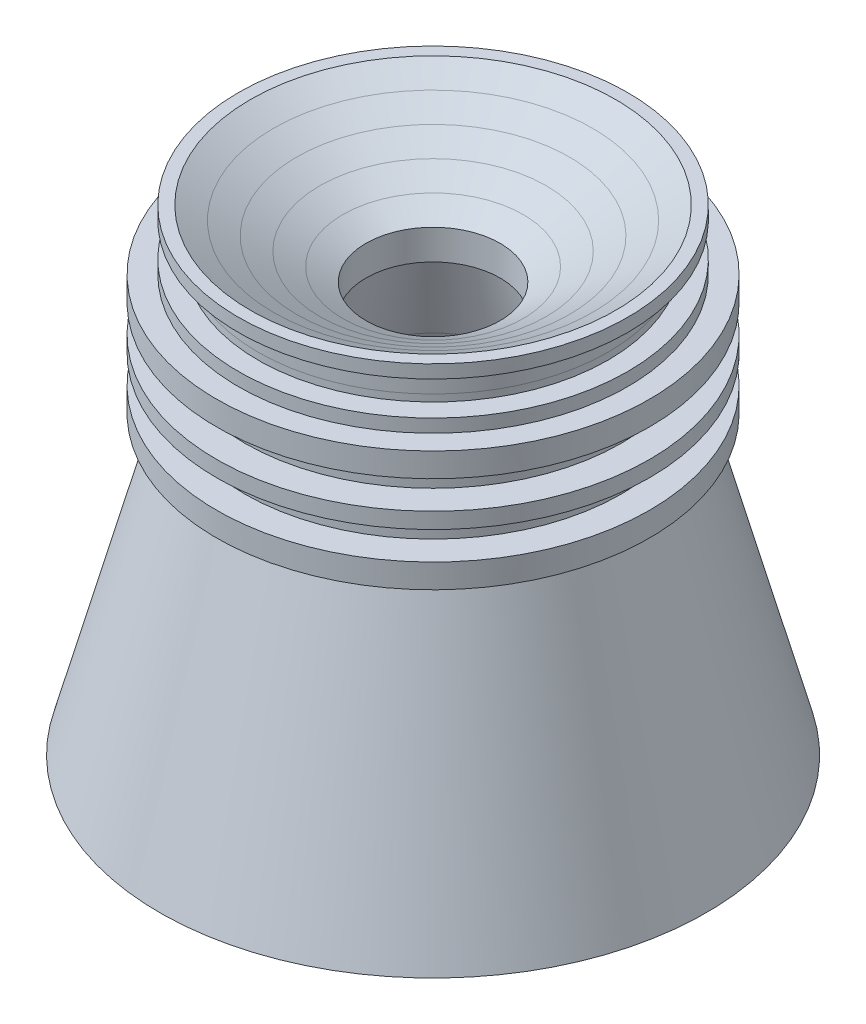
SolidWorks part; units mm, degrees
material "Copper"
ref_plane "Front Plane" through (0, 0, 0) normal (0, 0, 1) x (1, 0, 0)
ref_plane "Top Plane" through (0, 0, 0) normal (0, 1, 0) x (1, 0, 0)
ref_plane "Right Plane" through (0, 0, 0) normal (1, 0, 0) x (0, 0, -1)
sketch "Sketch1" plane through (0, 0, 0) normal (0, 0, 1) x (1, 0, 0)
  line L0 (0, 50.323) -> (0, -50.323) construction
  line L1 (41.1353, 50.323) -> (38.5953, 50.323)
  line L2 (38.5953, 50.323) -> (14.1732, 36.2228)
  line L3 (14.1732, 36.2228) -> (14.1732, 29.8728)
  line L4 (14.1732, 29.8728) -> (35.6616, -50.323)
  line L7 (41.0679, 11.9714) -> (41.1353, 12.223)
  line L9 (41.1353, 12.223) -> (45.7327, 12.223)
  line L10 (45.7327, 12.223) -> (45.7327, 37.623)
  line L11 (45.7327, 37.623) -> (41.1353, 37.623)
  line L12 (41.1353, 37.623) -> (41.1353, 50.323)
  line L13 (0, 50.323) -> (38.5953, 50.323) construction
  line L14 (41.0679, 11.9714) -> (57.7596, -50.323)
  line L15 (57.7596, -50.323) -> (35.6616, -50.323)
  line L16 (0, -50.323) -> (35.6616, -50.323) construction
  point P4 (0, 0)
  dimension "D1" = 41.1353
  dimension "D2" = 60
  dimension "D3" = 15
  dimension "D4" = 6.35
  dimension "D5" = 35.6616
  dimension "D6" = 14.1732
  dimension "D7" = 2.54
  dimension "D8" = 4.5974
  dimension "D9" = 22.098
  dimension "D10" = 150
  dimension "D11" = 12.7
  dimension "D12" = 25.4
revolve "Revolve1" add sketch "Sketch1" angle 360 about L0
sketch "Sketch2" plane through (0, 0, 0) normal (0, 0, 1) x (1, 0, 0)
  line L0 (45.7327, 12.223) -> (45.7327, 37.623) construction
  line L1 (41.1353, 47.5417) -> (36.9824, 47.5417)
  line L2 (41.1353, 47.5417) -> (41.1353, 40.4043)
  line L3 (41.1353, 40.4043) -> (36.9824, 40.4043)
  line L4 (36.9824, 47.5417) -> (36.9824, 40.4043)
  line L5 (45.7327, 32.543) -> (39.7915, 32.543)
  line L6 (45.7327, 32.543) -> (45.7327, 26.6018)
  line L7 (45.7327, 26.6018) -> (39.7915, 26.6018)
  line L8 (39.7915, 32.543) -> (39.7915, 26.6018)
  line L10 (45.7327, 23.2441) -> (39.7915, 23.2441)
  line L11 (45.7327, 23.2441) -> (45.7327, 17.303)
  line L12 (45.7327, 17.303) -> (39.7915, 17.303)
  line L13 (39.7915, 23.2441) -> (39.7915, 17.303)
  line L14 (41.1353, 50.323) -> (41.1353, 37.623) construction
  line L15 (45.7327, 37.623) -> (45.7327, 12.223) construction
  point P15 (41.1353, 43.973)
  point P24 (41.1353, 43.973)
  dimension "D1" = 7.1374
  dimension "D2" = 4.1529
  dimension "D3" = 5.08
  dimension "D4" = 5.08
revolve "Cut-Revolve1" cut sketch "Sketch2" angle 360 about axis through (0, 50.323, 0) along (0, 1, 0)
ref_plane "Plane1" through (0, 45.6229, 0) normal (0, 1, 0) x (1, 0, 0)
ref_plane "Plane2" through (0, 40.9229, 0) normal (0, 1, 0) x (1, 0, 0)
ref_plane "Plane3" through (0, 36.2229, 0) normal (0, 1, 0) x (1, 0, 0)
ref_plane "Plane4" through (0, 29.8729, 0) normal (0, 1, 0) x (1, 0, 0)
sketch "Sketch14" plane through (0, 0, 0) normal (0, 0, 1) x (1, 0, 0)
  line L0 (-50.4166, 29.8729) -> (50.3307, 29.8729)
  line L1 (50.4038, 29.8729) -> (-50.4038, 29.8729) construction
sketch "Sketch15" plane through (0, 0, 0) normal (0, 0, 1) x (1, 0, 0)
  line L0 (50.4038, 29.8729) -> (-50.4038, 29.8729) construction
  line L1 (-49.7252, 13.8338) -> (49.7252, 13.8338)
  point P0 (0, 13.8338)
  point P6 (0, 13.8338)
  dimension "D1" = 16.0392
sketch "Sketch16" plane through (0, 0, 0) normal (0, 0, 1) x (1, 0, 0)
  line L0 (50.4038, 29.8729) -> (-50.4038, 29.8729) construction
  line L1 (-51.2346, -2.2054) -> (51.2346, -2.2054)
  point P0 (0, -2.2054)
  point P6 (0, -2.2054)
  dimension "D1" = 32.0783
sketch "Sketch17" plane through (0, 0, 0) normal (0, 0, 1) x (1, 0, 0)
  line L0 (50.4038, 29.8729) -> (-50.4038, 29.8729) construction
  line L1 (-56.0981, -18.2446) -> (56.0981, -18.2446)
  point P0 (0, -18.2446)
  point P6 (0, -18.2446)
  dimension "D1" = 48.1175
sketch "Sketch18" plane through (0, 0, 0) normal (0, 0, 1) x (1, 0, 0)
  line L0 (50.4038, 29.8729) -> (-50.4038, 29.8729) construction
  line L1 (-60.3746, -34.2837) -> (60.3746, -34.2837)
  point P0 (0, -34.2837)
  point P6 (0, -34.2837)
  dimension "D1" = 64.1566
sketch "Sketch21" plane through (0, 0, 0) normal (0, 0, 1) x (1, 0, 0)
  line L0 (41.1353, 50.323) -> (-41.1353, 50.323) construction
  line L1 (-59.6067, 47.5029) -> (59.6067, 47.5029)
  point P0 (0, 47.5029)
  point P6 (0, 47.5029)
  dimension "D1" = 2.82
split line "Split Line17"
sketch "Sketch22" plane through (0, 0, 0) normal (0, 0, 1) x (1, 0, 0)
  line L0 (41.1353, 50.323) -> (-41.1353, 50.323) construction
  line L1 (-55.3935, 44.6829) -> (55.3935, 44.6829)
  point P0 (0, 44.6829)
  point P6 (0, 44.6829)
  dimension "D1" = 5.64
split line "Split Line18"
sketch "Sketch24" plane through (0, 0, 0) normal (0, 0, 1) x (1, 0, 0)
  line L0 (38.5953, 50.323) -> (-38.5953, 50.323) construction
  line L1 (-51.2809, 41.8629) -> (51.2809, 41.8629)
  point P0 (0, 41.8629)
  point P6 (0, 41.8629)
  dimension "D1" = 8.46
split line "Split Line19"
sketch "Sketch25" plane through (0, 0, 0) normal (0, 0, 1) x (1, 0, 0)
  line L0 (38.5953, 50.323) -> (-38.5953, 50.323) construction
  line L1 (-66.4722, 39.0429) -> (66.4722, 39.0429)
  point P0 (0, 39.0429)
  point P6 (0, 39.0429)
  dimension "D1" = 11.28
split line "Split Line20"
split line "Split Line21"
split line "Split Line22"
split line "Split Line23"
split line "Split Line24"
